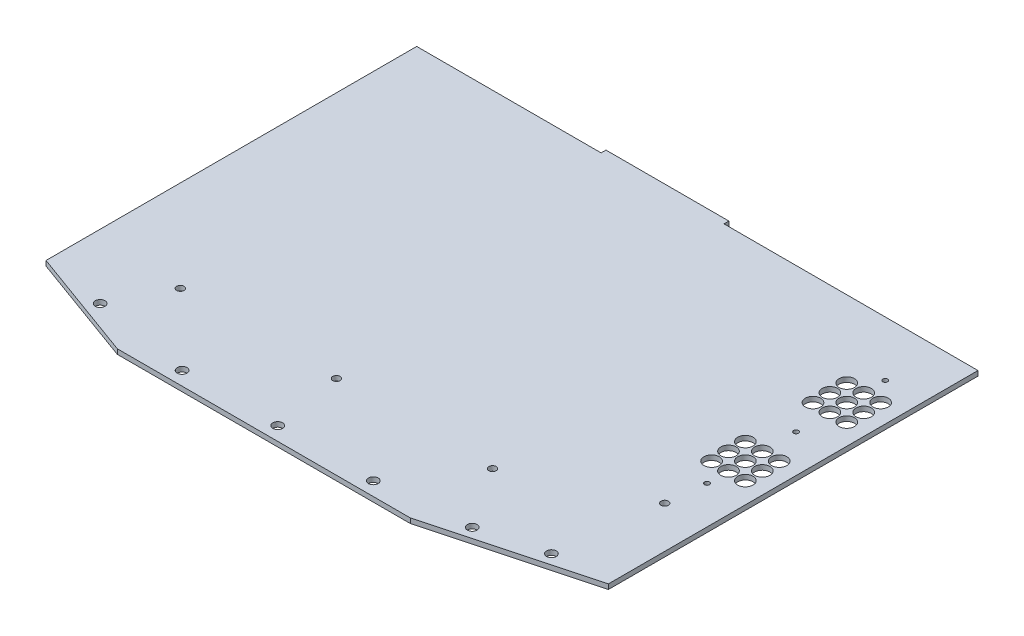
SolidWorks part; units mm, degrees
material "6061-T6 (SS)"
ref_plane "X-Y Datum" through (0, 0, 0) normal (0, 0, 1) x (1, 0, 0)
ref_plane "X-Z Datum" through (0, 0, 0) normal (0, 1, 0) x (1, 0, 0)
ref_plane "Y-Z Datum" through (0, 0, 0) normal (1, 0, 0) x (0, 0, -1)
sketch "Sketch1" plane through (0, 0, 0) normal (0, 0, 1) x (1, 0, 0)
  line L1 (-154.0408, -1.5875) -> (154.0408, -1.5875)
  line L2 (-154.0408, -1.5875) -> (-154.0408, 1.5875)
  line L3 (-154.0408, 1.5875) -> (154.0408, 1.5875)
  line L4 (154.0408, -1.5875) -> (154.0408, 1.5875)
  line L5 (-154.0408, -1.5875) -> (154.0408, 1.5875) construction
  line L6 (-154.0408, 1.5875) -> (154.0408, -1.5875) construction
  point P0 (0, 0)
  dimension "D1" = 3.175
  dimension "D2" = 308.0817
extrude "Boss-Extrude1" add sketch "Sketch1" along normal blind 267.83
sketch "Sketch3" plane through (154.0408, 0, 0) normal (1, 0, 0) x (0, 0, -1)
  line L9 (0, -1.5875) -> (0, 1.5875)
  line L10 (0, 1.5875) -> (-267.83, 1.5875)
  line L11 (-267.83, 1.5875) -> (-267.83, -1.5875)
  line L12 (-267.83, -1.5875) -> (0, -1.5875)
  line L13 (0, -1.5875) -> (0, 1.5875)
  line L14 (0, 1.5875) -> (-267.83, 1.5875)
  line L15 (-267.83, 1.5875) -> (-267.83, -1.5875)
  line L16 (-267.83, -1.5875) -> (0, -1.5875)
  dimension "D1" = 0
extrude "Boss-Extrude3" add sketch "Sketch3" along normal blind 3.175
sketch "Sketch4" plane through (0, 0, 267.83) normal (0, 0, 1) x (1, 0, 0)
  line L1 (157.2158, -1.5875) -> (208.1047, -1.5875)
  line L2 (157.2158, -1.5875) -> (157.2158, 1.5875)
  line L3 (157.2158, 1.5875) -> (208.1047, 1.5875)
  line L4 (208.1047, -1.5875) -> (208.1047, 1.5875)
  dimension "D1" = 3.175
  dimension "D2" = 50.8889
extrude "Boss-Extrude4" add sketch "Sketch4" against normal blind 267.83
sketch "Sketch6" plane through (0, 1.5875, 0) normal (0, 1, 0) x (1, 0, 0)
  line L0 (106.5047, -267.83) -> (106.5047, -223.38)
  line L1 (208.1047, -267.83) -> (-154.0408, -267.83) construction
  line L2 (208.1047, -223.38) -> (106.5047, -223.38)
  line L3 (208.1047, 0) -> (208.1047, -267.83) construction
  line L5 (106.5047, -267.83) -> (208.1047, -240.6064)
  line L7 (-154.0408, -267.83) -> (208.1047, -267.83) construction
  line L8 (208.1047, 0) -> (208.1047, -267.83) construction
  line L9 (208.1047, 0) -> (208.1047, -267.83)
  line M9 (-154.0408, -267.83) -> (208.1047, -267.83)
  line M10 (208.1047, -267.83) -> (208.1047, 0)
  dimension "D1" = 44.45
  dimension "D2" = 101.6
  dimension "D3" = 15
extrude "Cut-Extrude1" cut sketch "Sketch6" against normal through all contours L5 M9 M10
sketch "Sketch17" plane through (-154.0408, 0, 0) normal (-1, 0, 0) x (0, 0, 1)
  line L15 (267.83, -1.5875) -> (267.83, 1.5875)
  line L16 (0, -1.5875) -> (267.83, -1.5875)
  line L17 (267.83, -1.5875) -> (267.83, 1.5875)
  line L18 (267.83, 1.5875) -> (0, 1.5875)
  line L19 (0, 1.5875) -> (0, -1.5875)
  line L20 (0, -1.5875) -> (267.83, -1.5875)
  line L22 (267.83, 1.5875) -> (0, 1.5875)
  line L23 (0, 1.5875) -> (0, -1.5875)
  dimension "D1" = 0
extrude "Boss-Extrude5" add sketch "Sketch17" along normal blind 3.175
sketch "Sketch11" plane through (0, -1.5875, 0) normal (0, -1, 0) x (1, 0, 0)
  line L0 (-84.2547, 267.83) -> (-84.2547, 241.2743)
  line L1 (-157.2158, 267.83) -> (106.5047, 267.83) construction
  line L2 (-157.2158, 241.2743) -> (-84.2547, 241.2743)
  line L4 (-157.2158, 241.2743) -> (-84.2547, 267.83)
  line L6 (-157.2158, 267.83) -> (106.5047, 267.83) construction
  line L7 (-157.2158, 0) -> (-157.2158, 267.83) construction
  point P5 (0, 0)
  point P6 (0, 0)
  point P7 (-155.7756, 241.2743)
  point P8 (0, 0)
  point P9 (0, 0)
  point P10 (0, 0)
  point P11 (0, 0)
  point P12 (0, 0)
  point P13 (0, 0)
  point P14 (-93.6665, 241.2743)
  point P15 (0, 0)
  point P16 (0, 0)
  point P17 (0, 0)
  point P19 (0, 0)
  dimension "D2" = 26.5557
  dimension "D3" = 20
extrude "Cut-Extrude3" cut sketch "Sketch11" against normal through all
sketch "Sketch25" plane through (0, -1.5875, 0) normal (0, -1, 0) x (1, 0, 0)
  line L0 (-157.2285, 241.2697) -> (-83.9953, 267.9244) construction
  line L1 (-50.9753, 267.83) -> (-50.9753, 258.94)
  line L2 (-157.2158, 241.2743) -> (-84.2547, 267.83) construction
  line L3 (-118.0865, 255.5162) -> (-115.3222, 247.9214)
  line L5 (-84.2547, 267.83) -> (106.5047, 267.83) construction
  line L6 (-50.9753, 258.94) -> (11.2547, 258.94) construction
  line L7 (11.2547, 258.94) -> (73.4847, 258.94) construction
  line L8 (172.3981, 250.1739) -> (172.5447, 242.093)
  line L9 (106.5047, 267.83) -> (208.1047, 240.6064) construction
  line L10 (172.5447, 242.093) -> (131.9047, 252.9824) construction
  circle A0 centre (-115.3222, 247.9214) radius 3.175
  circle A1 centre (-50.9753, 258.94) radius 3.175
  circle A2 centre (11.2547, 258.94) radius 3.175
  circle A3 centre (73.4847, 258.94) radius 3.175
  circle A4 centre (172.5447, 242.093) radius 3.175
  circle A5 centre (131.9047, 252.9824) radius 3.175
  dimension "D2" = 90
  dimension "D3" = 6.35
  dimension "D13" = 8.89
  dimension "D4" = 7.7676
  dimension "D1" = 8.0823
  dimension "D5" = 33.02
  dimension "D6" = 62.23
  dimension "D7" = 62.23
  dimension "D8" = 33.02
  dimension "D9" = 35.56
  dimension "D10" = 73.96
  dimension "D11" = 40.64
  dimension "D12" = 8.0823
extrude "Cut-Extrude8" cut sketch "Sketch25" against normal blind 3.175
sketch "Sketch27" plane through (0, -1.5875, 0) normal (0, -1, 0) x (1, 0, 0)
  circle A0 centre (172.4867, 137.7748) radius 5 construction
  circle A1 centre (172.4867, 137.7748) radius 5
  circle A2 centre (183.4867, 137.7748) radius 5 construction
  circle A3 centre (183.4867, 137.7748) radius 5
  circle A4 centre (194.4867, 137.7748) radius 5 construction
  circle A5 centre (194.4867, 126.7748) radius 5 construction
  circle A6 centre (194.4867, 115.7748) radius 5 construction
  circle A7 centre (183.4867, 126.7748) radius 5 construction
  circle A8 centre (183.4867, 115.7748) radius 5 construction
  circle A9 centre (172.4867, 115.7748) radius 5 construction
  circle A10 centre (172.4867, 126.7748) radius 5 construction
  circle A11 centre (194.4867, 137.7748) radius 5
  circle A12 centre (194.4867, 126.7748) radius 5
  circle A13 centre (194.4867, 115.7748) radius 5
  circle A14 centre (183.4867, 126.7748) radius 5
  circle A15 centre (183.4867, 115.7748) radius 5
  circle A16 centre (172.4867, 115.7748) radius 5
  circle A17 centre (172.4867, 126.7748) radius 5
  circle A18 centre (194.4867, 71.7748) radius 5 construction
  circle A19 centre (194.4867, 60.7748) radius 5 construction
  circle A20 centre (194.4867, 49.7748) radius 5 construction
  circle A21 centre (183.4867, 71.7748) radius 5 construction
  circle A22 centre (183.4867, 60.7748) radius 5 construction
  circle A23 centre (183.4867, 49.7748) radius 5 construction
  circle A24 centre (172.4867, 49.7748) radius 5 construction
  circle A25 centre (172.4867, 60.7748) radius 5 construction
  circle A26 centre (172.4867, 71.7748) radius 5 construction
  circle A27 centre (194.4867, 71.7748) radius 5
  circle A28 centre (194.4867, 60.7748) radius 5
  circle A29 centre (194.4867, 49.7748) radius 5
  circle A30 centre (183.4867, 71.7748) radius 5
  circle A31 centre (183.4867, 60.7748) radius 5
  circle A32 centre (183.4867, 49.7748) radius 5
  circle A33 centre (172.4867, 49.7748) radius 5
  circle A34 centre (172.4867, 60.7748) radius 5
  circle A35 centre (172.4867, 71.7748) radius 5
extrude "Cut-Extrude9" cut sketch "Sketch27" against normal through all
sketch "Sketch30" plane through (0, 0, 0) normal (0, 0, -1) x (-1, 0, 0)
  line L0 (37.216, 1.5875) -> (37.216, -1.5875) construction
  line L1 (-42.784, 1.5875) -> (37.216, 1.5875) construction
  line L2 (-42.784, 1.5875) -> (-42.784, -1.5875) construction
  line L3 (37.216, 1.5875) -> (37.216, -1.5875)
  line L4 (-42.784, 1.5875) -> (37.216, 1.5875)
  line L5 (-42.784, 1.5875) -> (-42.784, -1.5875)
  line L6 (157.2158, -1.5875) -> (-208.1047, -1.5875) construction
  line L7 (157.2158, -1.5875) -> (-208.1047, -1.5875)
  line M1 (157.2158, 1.5875) -> (-208.1047, 1.5875)
  line M3 (-208.1047, -1.5875) -> (157.2158, -1.5875)
extrude "Boss-Extrude6" add sketch "Sketch30" along normal blind 3.175 contours L5 L3 M1 M3
sketch "Sketch31" plane through (0, -1.5875, 0) normal (0, -1, 0) x (1, 0, 0)
  circle A0 centre (183.4867, 151.7748) radius 2.4 construction
  circle A1 centre (183.4867, 151.7748) radius 2.4 construction
  circle A2 centre (183.4867, 151.7748) radius 1.5875
  dimension "D1" = 3.175
extrude "Cut-Extrude10" cut sketch "Sketch31" against normal through all both and the other way through all
pattern_linear "LPattern1" count 3 spacing 58 along (0, 0, -1) of "Cut-Extrude10"
sketch "Sketch34" plane through (0, -1.5875, 0) normal (0, -1, 0) x (1, 0, 0)
  point P0 (180.965, 176.776)
  point P1 (-97.7709, 213.285)
  point P2 (3.829, 213.285)
  point P3 (105.4291, 213.285)
hole_wizard "M4 Clearance Hole1" positions "Sketch34" profile "Sketch35" hole size "M4" standard "ANSI Metric" end condition through all
sketch "Sketch35" plane through (180.965, -1.5875, 176.776) normal (1, 0, 0) x (0, 0, -1)
  line L0 (0, 0) -> (0, 3.175)
  line L1 (0, 3.175) -> (2.4, 3.175)
  line L2 (2.4, 3.175) -> (2.4, 0)
  line L5 (2.4, 0) -> (0, 0)
  line L11 (0, -6.35) -> (0, 107.95) construction
  dimension "Thru Hole Dia." = 4.8
  dimension "Thru Hole Depth" = 3.175
